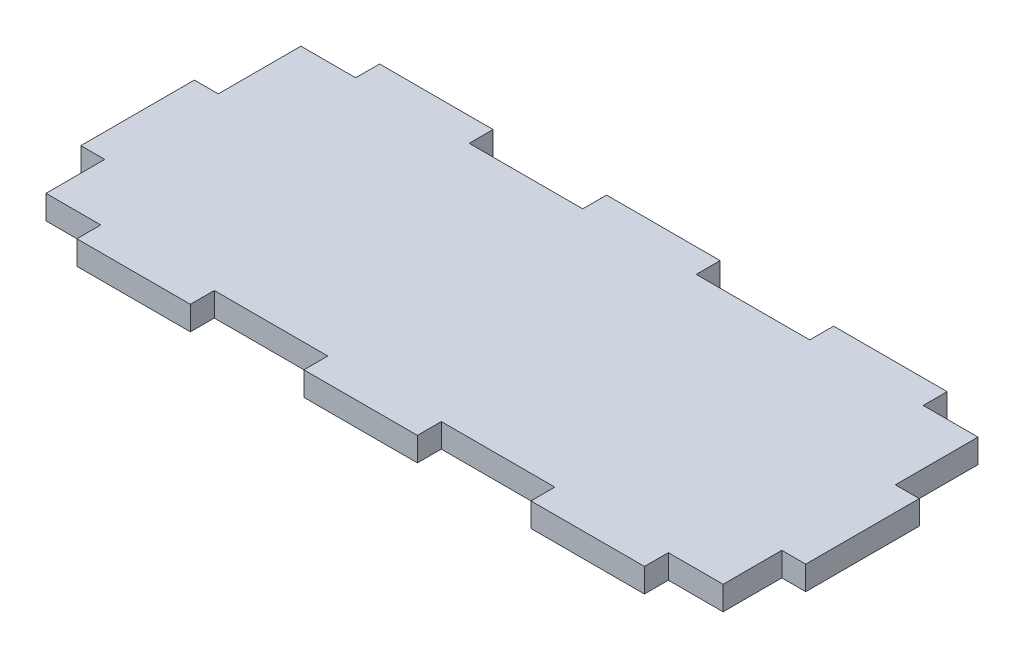
SolidWorks part; units mm, degrees
ref_plane "Front Plane" through (0, 0, 0) normal (0, 0, 1) x (1, 0, 0)
ref_plane "Top Plane" through (0, 0, 0) normal (0, 1, 0) x (1, 0, 0)
ref_plane "Right Plane" through (0, 0, 0) normal (1, 0, 0) x (0, 0, -1)
sketch "Sketch1" plane through (0, 0, 0) normal (0, 1, 0) x (1, 0, 0)
  line L72 (-41.5563, 14.2578) -> (-41.5563, 3.8828)
  line L73 (-41.5563, 3.8828) -> (-44.5563, 3.8828)
  line L74 (-44.5563, 3.8828) -> (-44.5563, -10.3672)
  line L75 (-44.5563, -10.3672) -> (-41.5563, -10.3672)
  line L76 (-41.5563, -10.3672) -> (-41.5563, -17.7422)
  line L77 (-41.5563, -17.7422) -> (-34.6813, -17.7422)
  line L78 (-34.6813, -17.7422) -> (-34.6813, -20.7422)
  line L79 (-34.6813, -20.7422) -> (-20.4313, -20.7422)
  line L80 (-20.4313, -20.7422) -> (-20.4313, -17.7422)
  line L81 (-20.4313, -17.7422) -> (-6.1813, -17.7422)
  line L82 (-6.1813, -17.7422) -> (-6.1813, -20.7422)
  line L83 (-6.1813, -20.7422) -> (8.0687, -20.7422)
  line L84 (8.0687, -20.7422) -> (8.0687, -17.7422)
  line L85 (8.0687, -17.7422) -> (22.3187, -17.7422)
  line L86 (22.3187, -17.7422) -> (22.3187, -20.7422)
  line L87 (22.3187, -20.7422) -> (36.5687, -20.7422)
  line L88 (36.5687, -20.7422) -> (36.5687, -17.7422)
  line L89 (36.5687, -17.7422) -> (43.4437, -17.7422)
  line L90 (43.4437, -17.7422) -> (43.4437, -10.3672)
  line L91 (43.4437, -10.3672) -> (46.4437, -10.3672)
  line L92 (46.4437, -10.3672) -> (46.4437, 3.8828)
  line L93 (46.4437, 3.8828) -> (43.4437, 3.8828)
  line L94 (43.4437, 3.8828) -> (43.4437, 14.2578)
  line L95 (43.4437, 14.2578) -> (36.5687, 14.2578)
  line L96 (36.5687, 14.2578) -> (36.5687, 17.2578)
  line L97 (36.5687, 17.2578) -> (22.3187, 17.2578)
  line L98 (22.3187, 17.2578) -> (22.3187, 14.2578)
  line L99 (22.3187, 14.2578) -> (8.0687, 14.2578)
  line L100 (8.0687, 14.2578) -> (8.0687, 17.2578)
  line L101 (8.0687, 17.2578) -> (-6.1813, 17.2578)
  line L102 (-6.1813, 17.2578) -> (-6.1813, 14.2578)
  line L103 (-6.1813, 14.2578) -> (-20.4313, 14.2578)
  line L104 (-20.4313, 14.2578) -> (-20.4313, 17.2578)
  line L105 (-20.4313, 17.2578) -> (-34.6813, 17.2578)
  line L106 (-34.6813, 17.2578) -> (-34.6813, 14.2578)
  line L107 (-34.6813, 14.2578) -> (-41.5563, 14.2578)
  dimension "D1" = 7.375
  dimension "D2" = 38
extrude "Boss-Extrude1" add sketch "Sketch1" along normal blind 3
